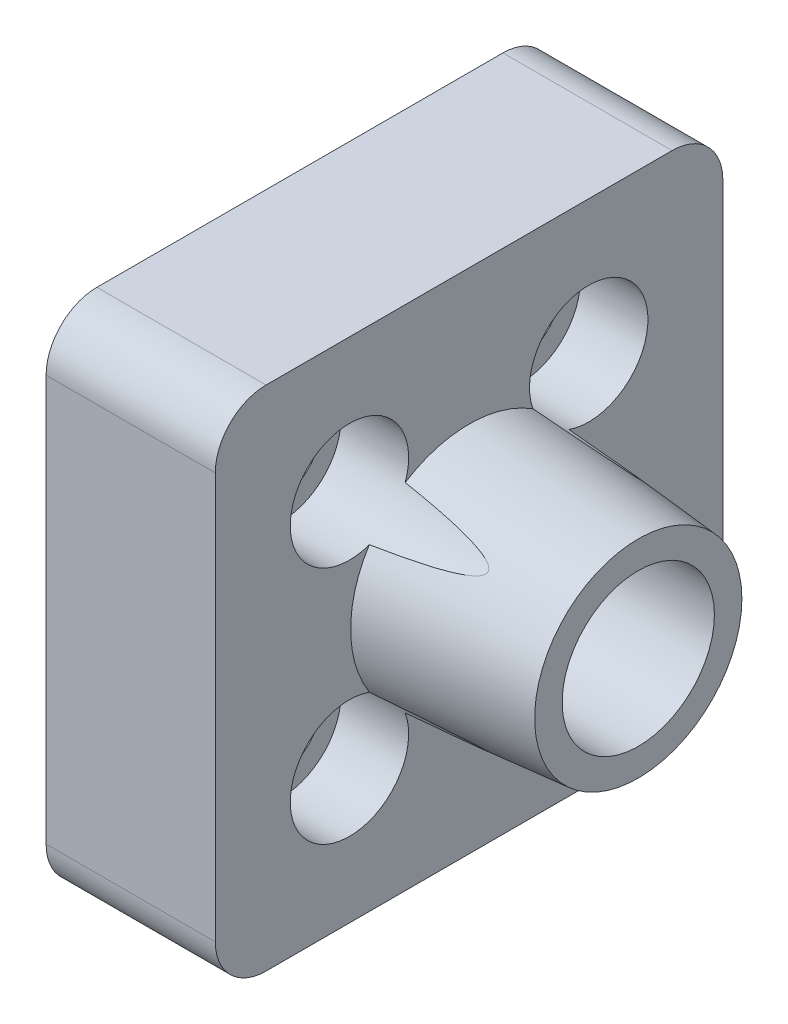
SolidWorks part; units mm, degrees
ref_plane "Ön Düzlem" through (0, 0, 0) normal (1, 0, 0) x (0, 1, 0)
ref_plane "Üst Düzlem" through (0, 0, 0) normal (0, 0, 1) x (0, 1, 0)
ref_plane "Sağ Düzlem" through (0, 0, 0) normal (0, 1, 0) x (-1, 0, 0)
sketch "Çizim1" plane through (0, 0, 0) normal (1, 0, 0) x (0, 1, 0)
  line L1 (15, 15) -> (-15, 15)
  line L2 (15, 15) -> (15, -15)
  line L3 (15, -15) -> (-15, -15)
  line L4 (-15, 15) -> (-15, -15)
  line L5 (15, 15) -> (-15, -15) construction
  line L6 (15, -15) -> (-15, 15) construction
  circle A0 centre (-7.0711, 7.0711) radius 2.25
  circle A1 centre (7.0711, 7.0711) radius 2.25
  circle A2 centre (7.0711, -7.0711) radius 2.25
  circle A3 centre (-7.0711, -7.0711) radius 2.25
  point P0 (0, 0)
  dimension "D4" = 4.5
  dimension "D1" = 30
  dimension "D2" = 30
  dimension "D3" = 10
  dimension "D5" = 4
extrude "Yükseklik-Ekstrüzyon1" add sketch "Çizim1" along normal blind 10
fillet "Radyus1" radius 3 4 edges at (5, -15, -15) (5, 15, -15) (5, 15, 15) (5, -15, 15)
sketch "Çizim2" plane through (10, 0, 0) normal (1, 0, 0) x (0, 1, 0)
  circle A0 centre (0, 0) radius 7
  dimension "D1" = 14
extrude "Yükseklik-Ekstrüzyon2" add sketch "Çizim2" along normal blind 10 draft 5
ref_plane "Düzlem1" through (0.8, 0, 0) normal (-1, 0, 0) x (0, -1, 0)
sketch "Çizim3" plane through (20, 0, 0) normal (1, 0, 0) x (0, 1, 0)
  circle A0 centre (0, 0) radius 4.5
  dimension "D1" = 9
extrude "Kes-Ekstrüzyon1" cut sketch "Çizim3" against normal through all
sketch "Çizim4" plane through (0.8, 0, 0) normal (-1, 0, 0) x (0, -1, 0)
  line L0 (13, -12) -> (13, 12)
  line L1 (12, 13) -> (-12, 13)
  line L2 (-13, 12) -> (-13, -12)
  line L3 (-12, -13) -> (12, -13)
  line L4 (-12, -15) -> (12, -15)
  line L5 (15, -12) -> (15, 12)
  line L6 (12, 15) -> (-12, 15)
  line L7 (-15, 12) -> (-15, -12)
  line L8 (-12, -15) -> (12, -15)
  line L9 (15, -12) -> (15, 12)
  line L10 (12, 15) -> (-12, 15)
  line L11 (-15, 12) -> (-15, -12)
  arc A0 (13, 12) -> (12, 13) centre (12, 12) ccw
  arc A1 (-12, 13) -> (-13, 12) centre (-12, 12) ccw
  arc A2 (-13, -12) -> (-12, -13) centre (-12, -12) ccw
  arc A3 (12, -13) -> (13, -12) centre (12, -12) ccw
  arc A4 (12, -15) -> (15, -12) centre (12, -12) ccw
  arc A5 (15, 12) -> (12, 15) centre (12, 12) ccw
  arc A6 (-12, 15) -> (-15, 12) centre (-12, 12) ccw
  arc A7 (-15, -12) -> (-12, -15) centre (-12, -12) ccw
  arc A8 (12, -15) -> (15, -12) centre (12, -12) ccw
  arc A9 (15, 12) -> (12, 15) centre (12, 12) ccw
  arc A10 (-12, 15) -> (-15, 12) centre (-12, 12) ccw
  arc A11 (-15, -12) -> (-12, -15) centre (-12, -12) ccw
  dimension "D1" = 0
  dimension "D2" = 2
sweep "Kes-Süpür2" cut path "Çizim4" circular profile diameter 2 parameters "D3"=2
sketch "Çizim34" plane through (10, 0, 0) normal (1, 0, 0) x (0, 1, 0)
  circle A0 centre (-7.0711, 7.0711) radius 3.5
  circle A1 centre (7.0711, 7.0711) radius 3.5
  circle A2 centre (7.0711, -7.0711) radius 3.5
  circle A3 centre (-7.0711, -7.0711) radius 3.5
  dimension "D1" = 7
extrude "Kes-Ekstrüzyon2" cut sketch "Çizim34" against normal blind 4 and the other way through all
